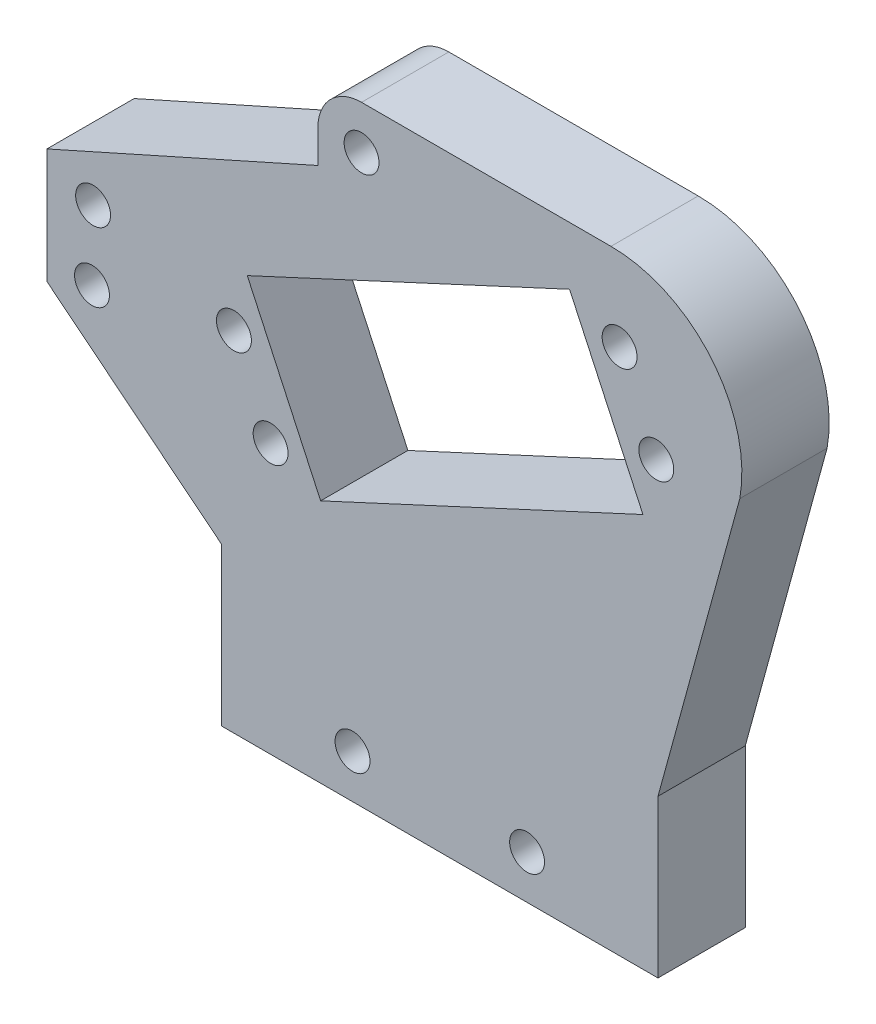
SolidWorks part; units mm, degrees
ref_plane "Piano frontale" through (0, 0, 0) normal (0, 0, 1) x (1, 0, 0)
ref_plane "Piano superiore" through (0, 0, 0) normal (0, 1, 0) x (1, 0, 0)
ref_plane "Piano destro" through (0, 0, 0) normal (1, 0, 0) x (0, 0, -1)
sketch "Schizzo1" plane through (0, 0, 0) normal (0, 0, 1) x (1, 0, 0)
  line L0 (15, -50) -> (-35, -50)
  line L1 (0, 0) -> (0, -50)
  line L2 (-35, -50) -> (-35, -31.9649)
  line L3 (-35, -31.9649) -> (-55.018, -15.8911)
  line L4 (-55.018, -15.8911) -> (-55.018, -2.7398)
  line L5 (-55.018, -2.7398) -> (-23.9664, 11.142)
  line L6 (-23.9664, 11.142) -> (-23.9664, 14.9096)
  line L7 (-18.9664, 19.9096) -> (9.6121, 19.9096)
  line L9 (15, -50) -> (15, -31.9649)
  line L10 (15, -31.9649) -> (24.3763, 2.2606)
  circle A0 centre (0, 0) radius 2.5
  arc A1 (9.6121, 19.9096) -> (24.3763, 2.2606) centre (9.6121, 4.9096) cw
  circle A2 centre (-20, -45) radius 2
  circle A3 centre (0, -45) radius 2
  circle A4 centre (-49.7259, -5.6899) radius 2
  circle A5 centre (-49.8508, -13.689) radius 2
  arc A6 (-23.9664, 14.9096) -> (-18.9664, 19.9096) centre (-18.9664, 14.9096) cw
  circle A7 centre (-18.9664, 14.9096) radius 2
  dimension "D1" = 5
  dimension "D5" = 15
  dimension "D6" = 4
  dimension "D7" = 4
  dimension "D11" = 4
  dimension "D12" = 4
  dimension "D14" = 5
  dimension "D15" = 4
  dimension "D2" = 50
  dimension "D3" = 50
  dimension "D4" = 15
  dimension "D8" = 15
  dimension "D9" = 5
  dimension "D10" = 5
  dimension "D13" = 8
extrude "Estrusione-Estrusione1" add sketch "Schizzo1" along normal blind 10
sketch "Schizzo2" plane through (0, 0, 10) normal (0, 0, 1) x (1, 0, 0)
  line L0 (0, 0) -> (-27.8561, -12.9046)
  line L1 (0, 0) -> (9.0736, 4.2034)
  line L3 (-23.6527, -21.9782) -> (13.2771, -4.8702)
  line L4 (-23.6527, -21.9782) -> (-32.0595, -3.8309)
  line L5 (-32.0595, -3.8309) -> (4.8702, 13.2771)
  line L6 (13.2771, -4.8702) -> (4.8702, 13.2771)
  point P9 (-27.8561, -12.9046)
  point P10 (9.0736, 4.2034)
  circle M13 centre (0, 0) radius 2.5
  dimension "D1" = 30.7
  dimension "D2" = 10
  dimension "D3" = 40.7
  dimension "D4" = 20
  dimension "D5" = 270
  dimension "D6" = 270
extrude "Taglio-Estrusione1" cut sketch "Schizzo2" against normal through all contours L1 L6 L5 L4 L0 M13 | L3 L6 L1 L0 L4 M13
sketch "Schizzo3" plane through (0, 0, 10) normal (0, 0, 1) x (1, 0, 0)
  line L0 (9.0736, 4.2034) -> (-27.8561, -12.9046) construction
  line L1 (-29.3838, -19.1228) -> (14.8048, 1.348)
  line L2 (-29.3838, -19.1228) -> (-33.5873, -10.0491)
  line L3 (-33.5873, -10.0491) -> (10.6014, 10.4216)
  line L4 (14.8048, 1.348) -> (10.6014, 10.4216)
  line L5 (-29.3838, -19.1228) -> (10.6014, 10.4216) construction
  line L6 (-33.5873, -10.0491) -> (14.8048, 1.348) construction
  line L7 (13.2771, -4.8702) -> (4.8702, 13.2771) construction
  line L8 (-23.6527, -21.9782) -> (-32.0595, -3.8309) construction
  line L9 (-13.5947, 4.7231) -> (-5.1878, -13.4242) construction
  line L10 (-32.0595, -3.8309) -> (4.8702, 13.2771) construction
  line L11 (-23.6527, -21.9782) -> (13.2771, -4.8702) construction
  circle A0 centre (10.6014, 10.4216) radius 2
  circle A1 centre (14.8048, 1.348) radius 2
  circle A2 centre (-29.3838, -19.1228) radius 2
  circle A3 centre (-33.5873, -10.0491) radius 2
  point P0 (-9.3912, -4.3506)
  point P17 (-9.3912, -4.3506)
  dimension "D6" = 4
  dimension "D7" = 4
  dimension "D8" = 4
  dimension "D9" = 4
  dimension "D1" = 4
  dimension "D2" = 10
  dimension "D3" = 270
  dimension "D4" = 270
  dimension "D5" = 270
  dimension "D10" = 4
extrude "Taglio-Estrusione2" cut sketch "Schizzo3" against normal through all contours A3 | A2 | A1 | A0
